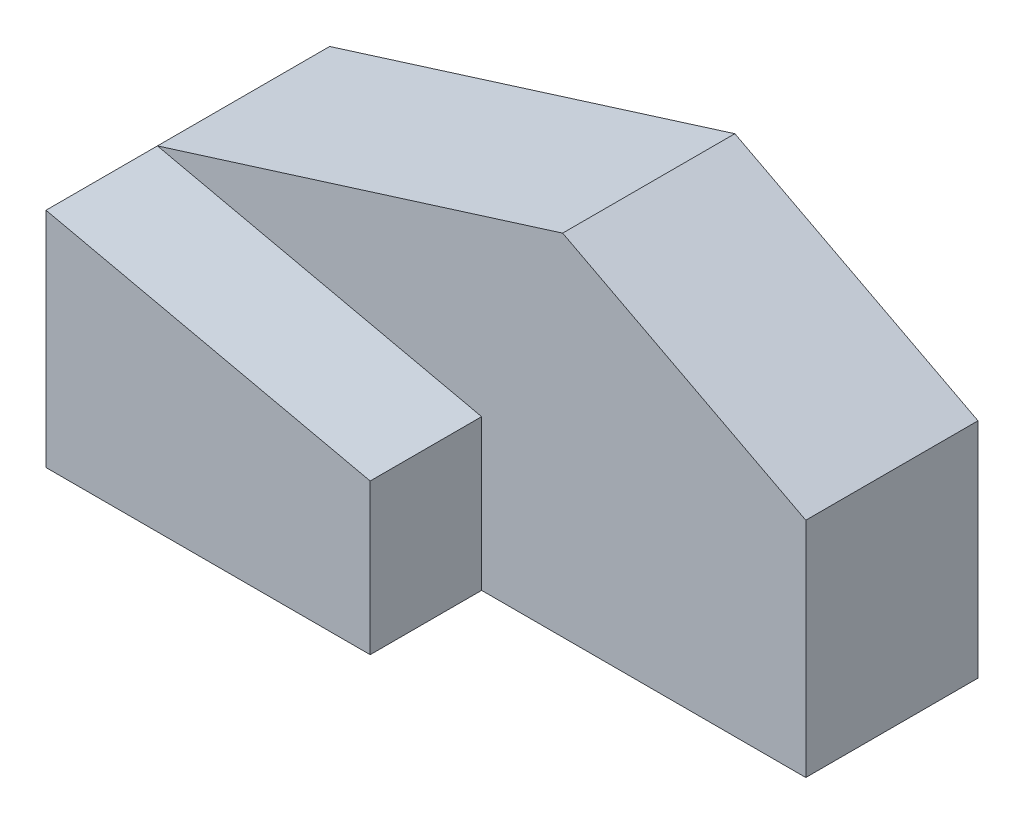
SolidWorks part; units mm, degrees
ref_plane "Front Plane" through (0, 0, 0) normal (0, 0, 1) x (1, 0, 0)
ref_plane "Top Plane" through (0, 0, 0) normal (0, 1, 0) x (1, 0, 0)
ref_plane "Right Plane" through (0, 0, 0) normal (1, 0, 0) x (0, 0, -1)
sketch "Sketch1" plane through (0, 0, 0) normal (0, 0, 1) x (1, 0, 0)
  line L0 (-50.8, 0) -> (50.8, 0)
  line L1 (-50.8, 0) -> (-50.8, -34.925)
  line L2 (-50.8, -34.925) -> (50.8, -34.925)
  line L3 (50.8, -34.925) -> (50.8, 0)
  line L4 (-50.8, 0) -> (12.7, 19.9106)
  line L5 (12.7, 19.9106) -> (50.8, 0)
  point P4 (0, 0)
  dimension "D1" = 63.5
  dimension "D2" = 135
  dimension "D3" = 101.6
  dimension "D4" = 34.925
extrude "Boss-Extrude2" add sketch "Sketch1" along normal blind 26.9875 contours L5 L4 L0 | L2 L3 L0 L1
sketch "Sketch3" plane through (0, 0, 26.9875) normal (0, 0, 1) x (1, 0, 0)
  line L0 (-50.8, 0) -> (0, -11.3468)
  line L1 (0, -11.3468) -> (0, -34.925)
  line L2 (-50.8, -34.925) -> (50.8, -34.925) construction
  line L3 (0, -34.925) -> (-50.8, -34.925)
  line L4 (-50.8, -34.925) -> (-50.8, 0)
  line L7 (-50.8, 0) -> (12.7, 19.9106) construction
  dimension "D1" = 50.8
  dimension "D2" = 30
extrude "Boss-Extrude3" add sketch "Sketch3" along normal blind 17.4625 contours L4 L0 L1 L3
